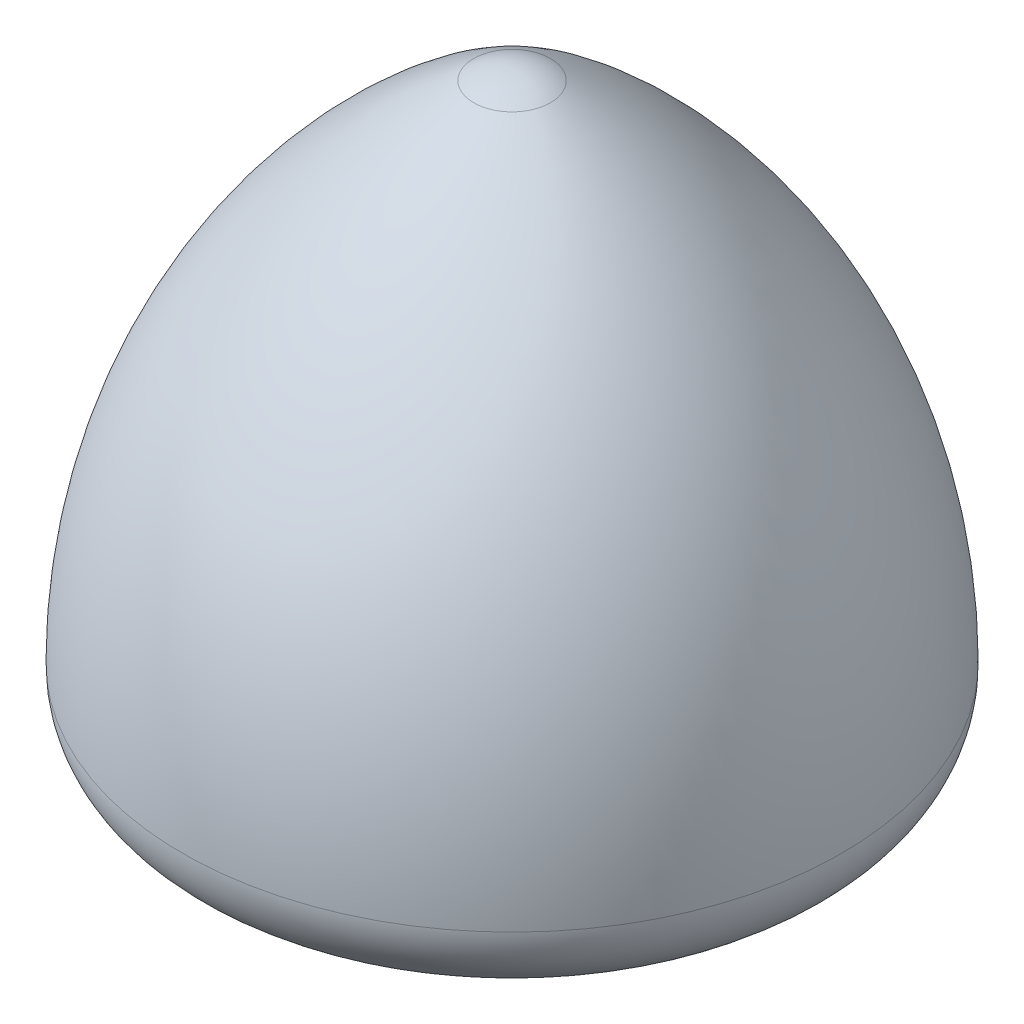
SolidWorks part; units mm, degrees
ref_plane "Front Plane" through (0, 0, 0) normal (0, 0, 1) x (1, 0, 0)
ref_plane "Top Plane" through (0, 0, 0) normal (0, 1, 0) x (1, 0, 0)
ref_plane "Right Plane" through (0, 0, 0) normal (1, 0, 0) x (0, 0, -1)
sketch "Sketch1" plane through (0, 0, 0) normal (0, 0, 1) x (1, 0, 0)
  line L0 (0, 0) -> (0, 20.7367) construction
  line L1 (-3.7406, 15.6696) -> (-15.9325, -5.4473) construction
  line L2 (-11.7, -11.0743) -> (12.6838, -11.0743) construction
  line L3 (15.4406, -4.5953) -> (3.2487, 16.5216) construction
  line L4 (0, 27.9673) -> (0, -22.0327)
  circle A0 centre (0, 0) radius 11.0743 construction
  arc A1 (2.9094, 27.1878) -> (25, -11.0743) centre (-19.1812, -11.0743) cw
  arc A2 (25, -11.0743) -> (22.0906, -16.1135) centre (19.1812, -11.0743) cw
  arc A3 (22.0906, -16.1135) -> (0, -22.0327) centre (0, 22.1485) cw
  arc A4 (2.9094, 27.1878) -> (0, 27.9673) centre (0, 22.1485) ccw
  dimension "D1" = 50
revolve "Revolve1" add sketch "Sketch1" angle 360 about L0
scale "Scale1" scale about centroid uniform scaling yes scale factor 0.5
